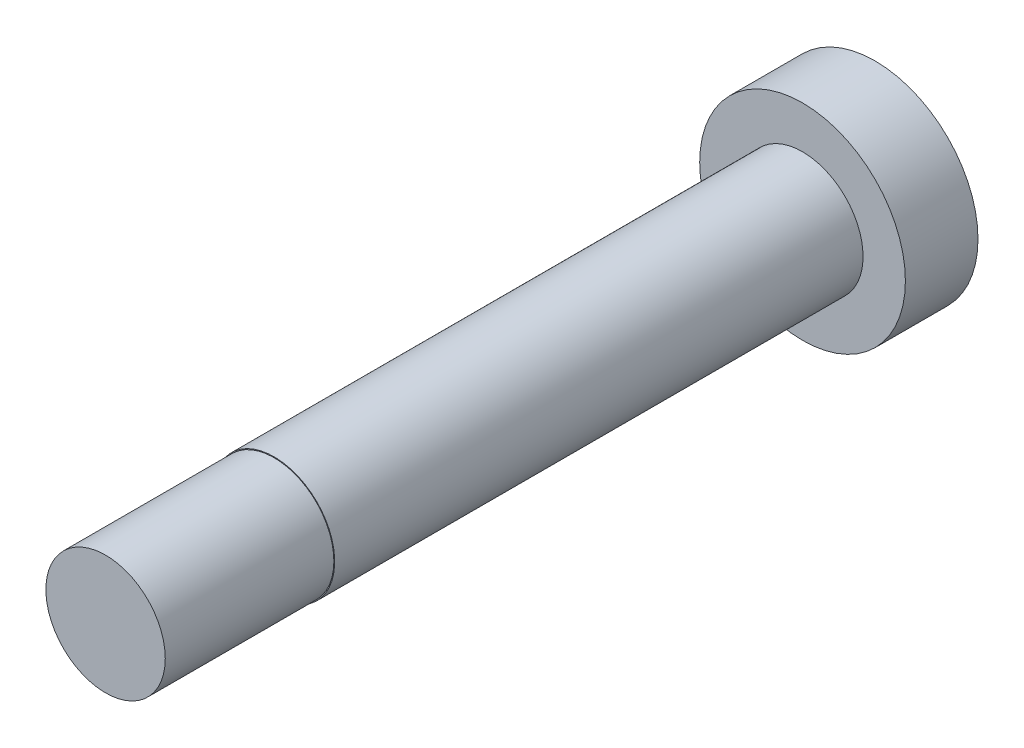
SolidWorks part; units mm, degrees
ref_plane "Front Plane" through (0, 0, 0) normal (0, 0, 1) x (1, 0, 0)
ref_plane "Top Plane" through (0, 0, 0) normal (0, 1, 0) x (1, 0, 0)
ref_plane "Right Plane" through (0, 0, 0) normal (1, 0, 0) x (0, 0, -1)
sketch "S01 - Low profile head" plane through (0, 0, 0) normal (0, 0, 1) x (1, 0, 0)
  circle A0 centre (0, 0) radius 2.55
  dimension "D1" = 5.1
extrude "01 - Low profile head" add sketch "S01 - Low profile head" along normal blind 1.8 from offset 1.8
sketch "S02 - Smooth journal" plane through (0, 0, 0) normal (0, 0, 1) x (1, 0, 0)
  circle A0 centre (0, 0) radius 1.5
  dimension "D1" = 3
extrude "02 - Smooth journal" add sketch "S02 - Smooth journal" along normal blind 13.1
sketch "S03 - M3 threaded tip" plane through (0, 0, 0) normal (0, 0, 1) x (1, 0, 0)
  circle A0 centre (0, 0) radius 1.48
  dimension "D1" = 2.96
extrude "03 - M3 threaded tip" add sketch "S03 - M3 threaded tip" along normal blind 4.18 from offset 13.1
sketch "S04 - Hex socket" plane through (0, 0, 0) normal (0, 0, 1) x (1, 0, 0)
  line L0 (0.9959, 0.575) -> (0, 1.15)
  line L1 (0, 1.15) -> (-0.9959, 0.575)
  line L2 (-0.9959, 0.575) -> (-0.9959, -0.575)
  line L3 (-0.9959, -0.575) -> (0, -1.15)
  line L4 (0, -1.15) -> (0.9959, -0.575)
  line L5 (0.9959, -0.575) -> (0.9959, 0.575)
  dimension "D1" = 0.9959
  dimension "D2" = 0.9959
  dimension "D3" = 0.575
  dimension "D4" = 1.15
  dimension "D5" = 0.575
  dimension "D6" = 1.15
extrude "04 - Hex socket" cut sketch "S04 - Hex socket" along normal blind 1.05 from offset 1.9
